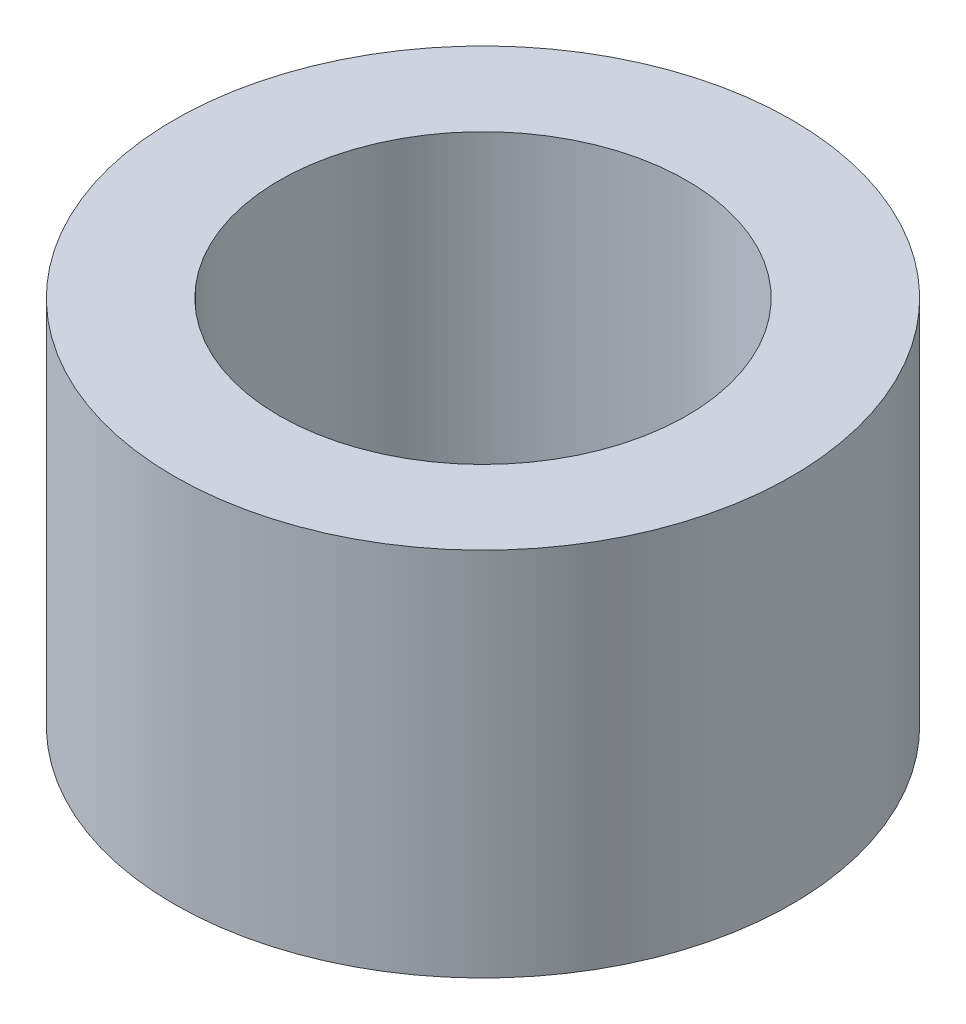
SolidWorks part; units mm, degrees
ref_plane "前视基准面" through (0, 0, 0) normal (0, 0, 1) x (1, 0, 0)
ref_plane "上视基准面" through (0, 0, 0) normal (0, 1, 0) x (1, 0, 0)
ref_plane "右视基准面" through (0, 0, 0) normal (1, 0, 0) x (0, 0, -1)
sketch "草图1" plane through (0, 0, 0) normal (0, 1, 0) x (1, 0, 0)
  circle A0 centre (0, 0) radius 1.65
  circle A1 centre (0, 0) radius 2.5
  dimension "D1" = 3.3
  dimension "D2" = 5
extrude "凸台-拉伸1" add sketch "草图1" along normal blind 3
equation "\"m\"= 2"
